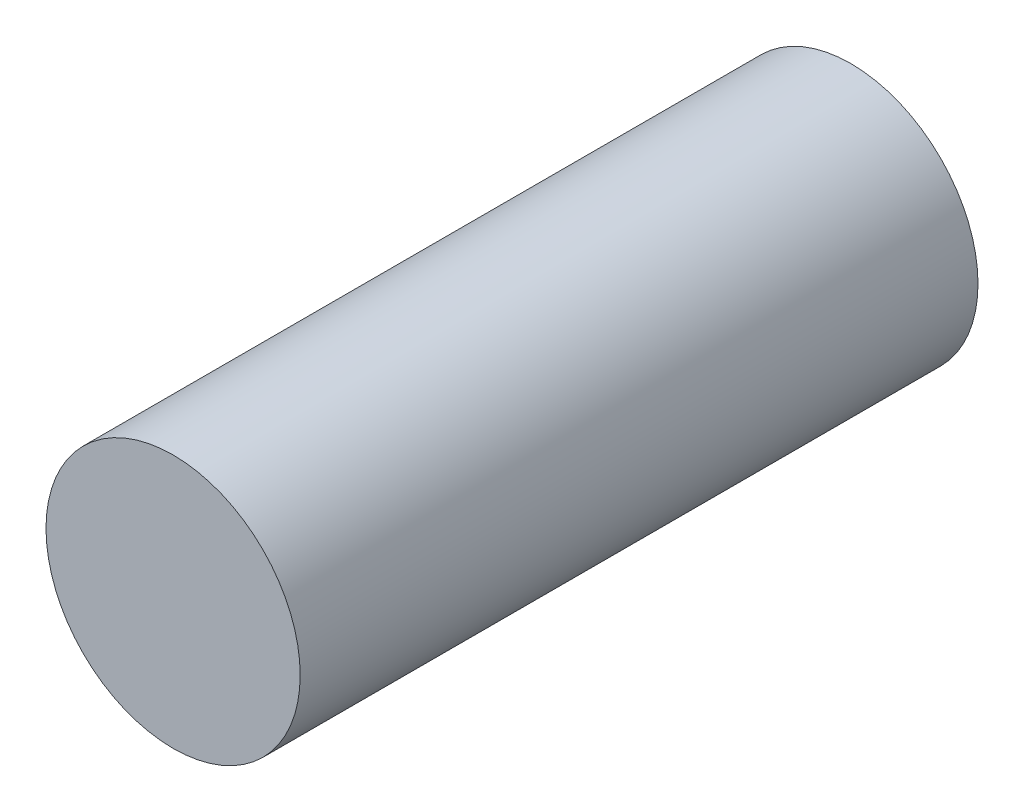
SolidWorks part; units mm, degrees
ref_plane "Front Plane" through (0, 0, 0) normal (1, 0, 0) x (0, 1, 0)
ref_plane "Top Plane" through (0, 0, 0) normal (0, 0, 1) x (0, 1, 0)
ref_plane "Right Plane" through (0, 0, 0) normal (0, 1, 0) x (-1, 0, 0)
sketch "Sketch2" plane through (0, 0, 0) normal (0, 0, 1) x (0, 1, 0)
  circle A0 centre (0, 0) radius 7.62
  dimension "D1" = 15.24
extrude "Boss-Extrude1" add sketch "Sketch2" along normal blind 40.64
